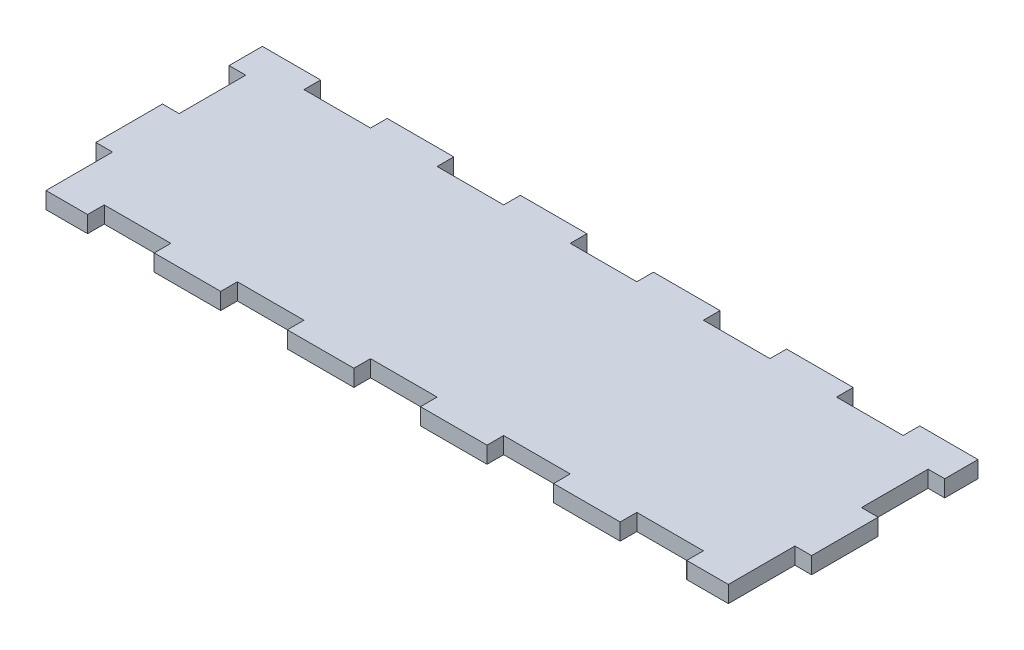
SolidWorks part; units mm, degrees
ref_plane "정면" through (0, 0, 0) normal (0, 0, 1) x (1, 0, 0)
ref_plane "윗면" through (0, 0, 0) normal (0, 1, 0) x (1, 0, 0)
ref_plane "우측면" through (0, 0, 0) normal (1, 0, 0) x (0, 0, -1)
sketch "스케치1" plane through (0, 0, 0) normal (0, 1, 0) x (1, 0, 0)
  line L1 (-107.5, 35) -> (107.5, 35)
  line L2 (-107.5, 35) -> (-107.5, -35)
  line L3 (-107.5, -35) -> (107.5, -35)
  line L4 (107.5, 35) -> (107.5, -35)
  line L5 (-107.5, 35) -> (107.5, -35) construction
  line L6 (-107.5, -35) -> (107.5, 35) construction
  point P0 (0, 0)
  dimension "D1" = 70
  dimension "D2" = 215
extrude "보스-돌출1" add sketch "스케치1" along normal blind 5
sketch "스케치2" plane through (0, 5, 0) normal (0, 1, 0) x (1, 0, 0)
  line L0 (-107.5, -35) -> (107.5, -35) construction
  line L1 (-10, -35) -> (10, -35)
  line L2 (-10, -35) -> (-10, -30)
  line L3 (-10, -30) -> (10, -30)
  line L4 (10, -35) -> (10, -30)
  line L5 (0, 1.9938) -> (0, -61.9938) construction
  point P9 (0, -30)
  dimension "D1" = 5
  dimension "D2" = 20
extrude "컷-돌출1" cut sketch "스케치2" against normal up to next
pattern_linear "선형 패턴1" count 3 spacing 40 along (1, 0, 0) of "컷-돌출1"
pattern_linear "선형 패턴2" count 3 spacing 40 along (-1, 0, 0) of "컷-돌출1"
sketch "스케치3" plane through (0, 5, 0) normal (0, 1, 0) x (1, 0, 0)
  line L1 (107.5, -35) -> (102.5, -35)
  line L2 (107.5, -35) -> (107.5, -15)
  line L3 (107.5, -15) -> (102.5, -15)
  line L4 (102.5, -35) -> (102.5, -15)
  dimension "D1" = 5
  dimension "D2" = 20
extrude "컷-돌출2" cut sketch "스케치3" against normal up to next
pattern_linear "선형 패턴3" count 2 spacing 40 along (0, 0, -1) of "컷-돌출2"
mirror "대칭 복사1" about plane through (0, 0, 0) normal (1, 0, 0) of "선형 패턴3", "컷-돌출2"
mirror "대칭 복사3" about plane through (0, 0, 0) normal (0, 0, 1) of "선형 패턴1", "선형 패턴2", "컷-돌출1"
